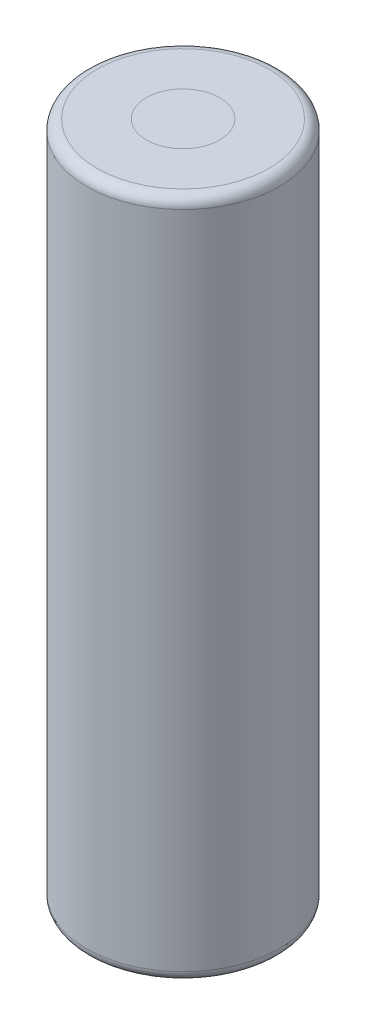
SolidWorks part; units mm, degrees
ref_plane "Front Plane" through (0, 0, 0) normal (0, 0, 1) x (1, 0, 0)
ref_plane "Top Plane" through (0, 0, 0) normal (0, 1, 0) x (1, 0, 0)
ref_plane "Right Plane" through (0, 0, 0) normal (1, 0, 0) x (0, 0, -1)
sketch "Sketch1" plane through (0, 0, 0) normal (0, 1, 0) x (1, 0, 0)
  circle A0 centre (0, 0) radius 9.2
  dimension "D1" = 18.4
extrude "Boss-Extrude1" add sketch "Sketch1" along normal mid plane 65
fillet "Fillet1" radius 1 2 edges at (0, -32.5, 9.2) (0, 32.5, 9.2)
sketch "Sketch2" plane through (0, 32.5, 0) normal (0, 1, 0) x (1, 0, 0)
  circle A0 centre (0, 0) radius 3.5
  circle A1 centre (0, 0) radius 8.2 construction
  dimension "D1" = 7
split line "Split Line1"
